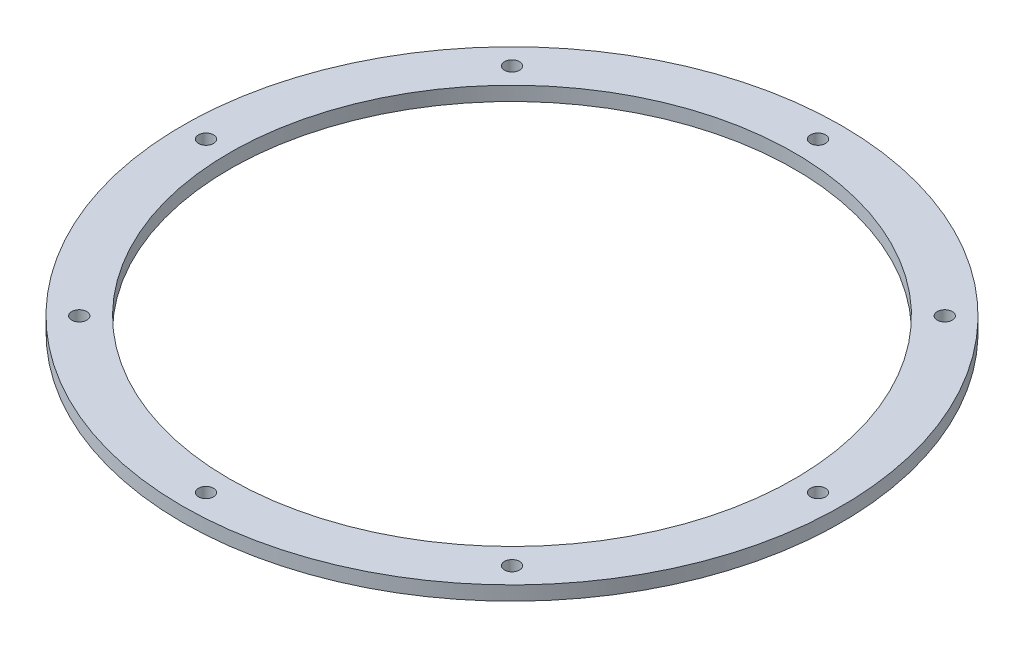
SolidWorks part; units mm, degrees
ref_plane "Front Plane" through (0, 0, 0) normal (0, 0, 1) x (1, 0, 0)
ref_plane "Top Plane" through (0, 0, 0) normal (0, 1, 0) x (1, 0, 0)
ref_plane "Right Plane" through (0, 0, 0) normal (1, 0, 0) x (0, 0, -1)
sketch "Sketch1" plane through (0, 0, 0) normal (0, 1, 0) x (1, 0, 0)
  circle A1 centre (0, 0) radius 60
  circle A2 centre (0, 0) radius 65 construction
  circle A3 centre (0, 0) radius 70
  circle A4 centre (0, 65) radius 1.6
  circle A5 centre (45.9619, 45.9619) radius 1.6
  circle A6 centre (65, 0) radius 1.6
  circle A7 centre (45.9619, -45.9619) radius 1.6
  circle A8 centre (0, -65) radius 1.6
  circle A9 centre (-45.9619, -45.9619) radius 1.6
  circle A10 centre (-65, 0) radius 1.6
  circle A11 centre (-45.9619, 45.9619) radius 1.6
  point P24 (0, 0)
  dimension "D1" = 120
  dimension "D2" = 5
  dimension "D3" = 5
  dimension "D4" = 3.2
  dimension "D5" = 8
extrude "Boss-Extrude1" add sketch "Sketch1" along normal blind 3
